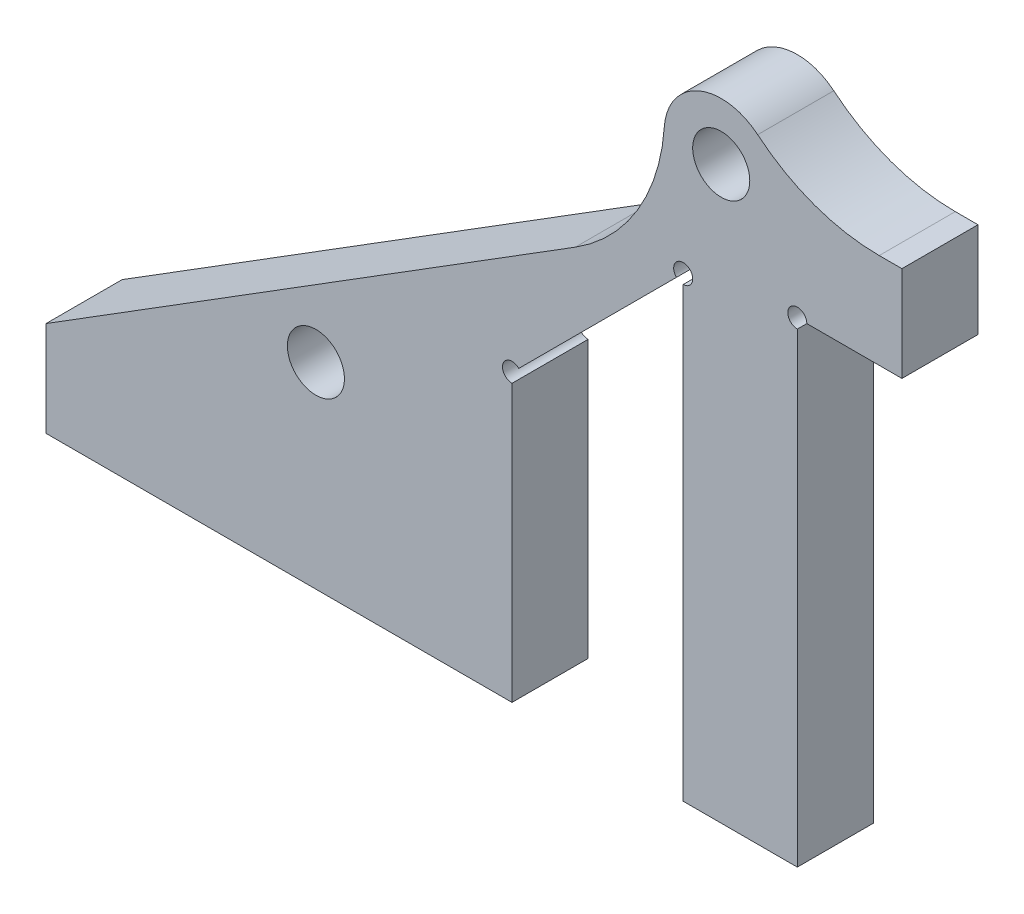
SolidWorks part; units mm, degrees
material "PMMA"
ref_plane "前视基准面" through (0, 0, 0) normal (0, 0, 1) x (1, 0, 0)
ref_plane "上视基准面" through (0, 0, 0) normal (0, 1, 0) x (1, 0, 0)
ref_plane "右视基准面" through (0, 0, 0) normal (1, 0, 0) x (0, 0, -1)
other "Configuration Table"
sketch "草图1" plane through (0, 0, 0) normal (0, 0, 1) x (1, 0, 0)
  line L0 (-5.5, 0) -> (-11.5, 0)
  line L1 (-45, 0) -> (-45, 5)
  line L2 (-45, 5) -> (-5, 30)
  line L3 (-5, 30) -> (0, 30)
  line L4 (0, 30) -> (0, 25)
  line L5 (-20.5, 0) -> (-20.5, 15.03)
  line L6 (-20.5, 15.03) -> (-11.5, 24.03)
  line L7 (-11.5, 24.03) -> (-11.5, 0)
  line L8 (-5.5, 0) -> (-5.5, 25)
  line L9 (-5.5, 25) -> (0, 25)
  line L10 (-20.5, 0) -> (-45, 0)
  line L11 (0, 25) -> (0, 0) construction
  line L12 (0, 0) -> (-5.5, 0) construction
  line L13 (-11.5, 0) -> (-20.5, 0) construction
  dimension "D1" = 5
  dimension "D2" = 5
  dimension "D3" = 30
  dimension "D4" = 9
  dimension "D5" = 6
  dimension "D6" = 5.5
  dimension "D7" = 24.03
  dimension "D8" = 25
  dimension "D9" = 45
  dimension "D10" = 45
extrude "凸台-拉伸1" add sketch "草图1" along normal blind 4
sketch "草图2" plane through (0, 0, 4) normal (0, 0, 1) x (1, 0, 0)
  line L0 (-5, 30) -> (-9.5, 30) construction
  line L1 (-9.5, 30) -> (-9.5, 27.1875) construction
  line L2 (-5, 30) -> (-45, 5) construction
  line L3 (-6.5, 30) -> (-5, 30)
  line L4 (-12.5, 30) -> (-12.5, 25.3125)
  line L5 (-5, 30) -> (-12.5, 25.3125)
  circle A0 centre (-9.5, 30) radius 1.5
  arc A1 (-6.5, 30) -> (-12.5, 30) centre (-9.5, 30) ccw
  dimension "D2" = 3
  dimension "D3" = 3
  dimension "D1" = 4.5
extrude "凸台-拉伸2" add sketch "草图2" against normal blind 4
sketch "草图3" plane through (0, 0, 4) normal (0, 0, 1) x (1, 0, 0)
  line L0 (-30.8102, 10.3309) -> (-32.4002, 12.8749) construction
  line L1 (-12.5, 25.3125) -> (-45, 5) construction
  circle A0 centre (-30.8102, 10.3309) radius 1.5
  circle A1 centre (-9.5, 30) radius 1.5 construction
  dimension "D1" = 3
  dimension "D2" = 3
  dimension "D3" = 29
extrude "切除-拉伸1" cut sketch "草图3" against normal blind 4
fillet "圆角1" radius 10 2 edges at (-6.5, 30, 2) (-12.5, 25.3125, 2)
sketch "草图4" plane through (0, 0, 4) normal (0, 0, 1) x (1, 0, 0)
  circle A0 centre (-5.5, 25) radius 0.5
  circle A1 centre (-11.5, 24.03) radius 0.5
  circle A2 centre (-20.5, 15.03) radius 0.5
  dimension "D1" = 1
  dimension "D2" = 1
  dimension "D3" = 1
extrude "切除-拉伸2" cut sketch "草图4" against normal blind 4
